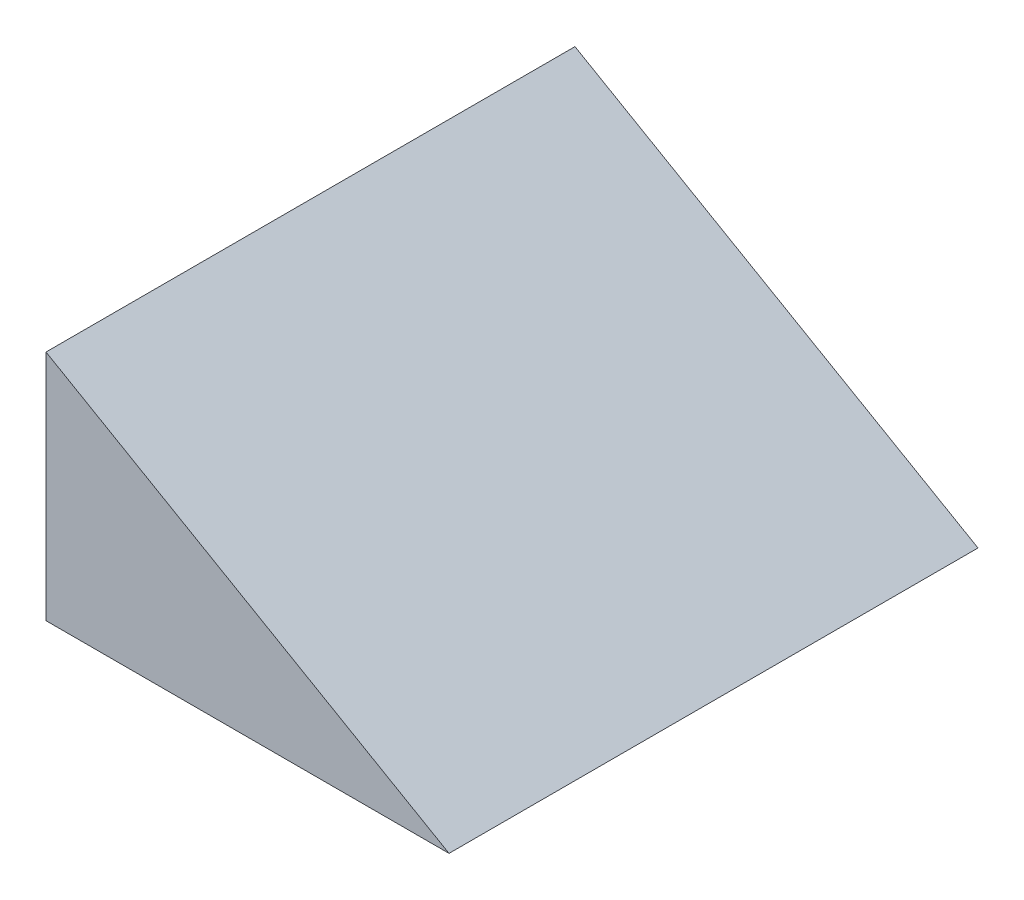
SolidWorks part; units mm, degrees
ref_plane "Front Plane" through (0, 0, 0) normal (0, 0, 1) x (1, 0, 0)
ref_plane "Top Plane" through (0, 0, 0) normal (0, 1, 0) x (1, 0, 0)
ref_plane "Right Plane" through (0, 0, 0) normal (1, 0, 0) x (0, 0, -1)
sketch "Sketch1" plane through (0, 0, 0) normal (0, 0, 1) x (1, 0, 0)
  line L0 (16, 0) -> (0, 9.2376)
  line L1 (0, 0) -> (16, 0)
  line L2 (0, 0) -> (0, 9.2376)
  line L3 (0, 32.9023) -> (16, 32.9023)
extrude "Boss-Extrude1" add sketch "Sketch1" along normal blind 21 contours L2 L0 L1
